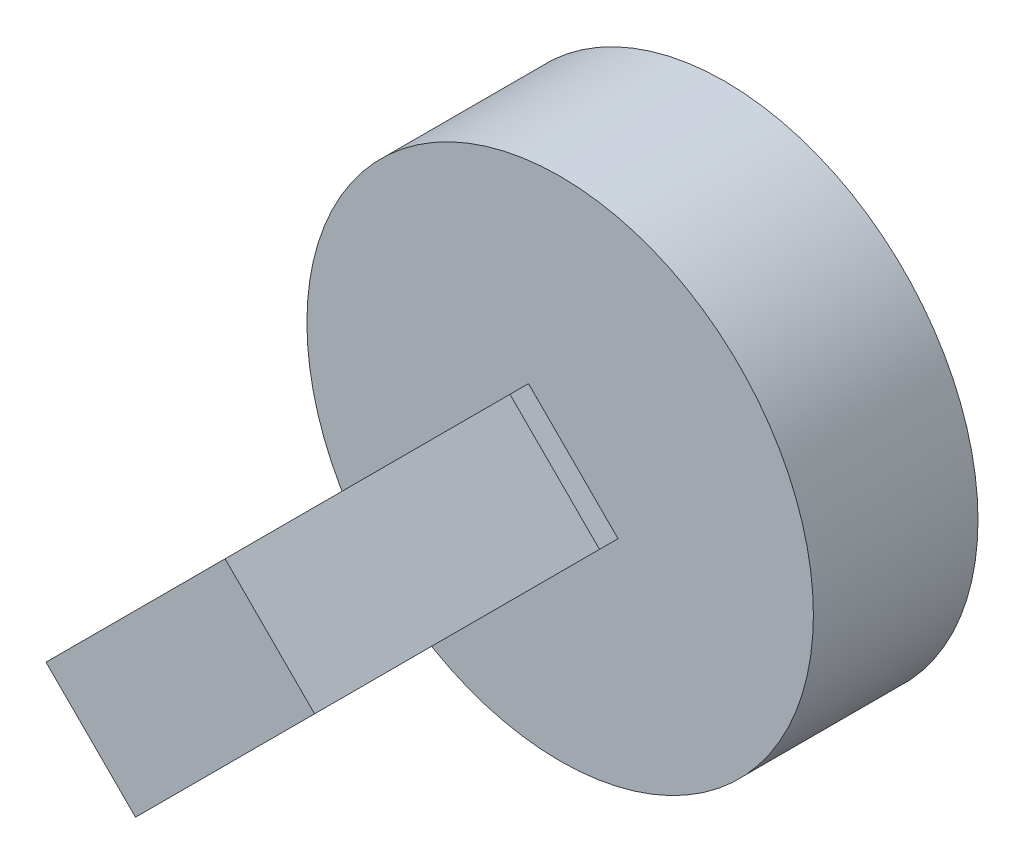
SolidWorks part; units mm, degrees
ref_plane "前视基准面" through (0, 0, 0) normal (0, 0, 1) x (1, 0, 0)
ref_plane "上视基准面" through (0, 0, 0) normal (0, 1, 0) x (1, 0, 0)
ref_plane "右视基准面" through (0, 0, 0) normal (1, 0, 0) x (0, 0, -1)
sketch "草图1" plane through (0, 0, 0) normal (0, 0, 1) x (1, 0, 0)
  circle A0 centre (0, 0) radius 40
extrude "凸台-拉伸1" add sketch "草图1" along normal blind 26
sketch "草图2" plane through (0, 0, 26) normal (0, 0, 1) x (1, 0, 0)
  circle A0 centre (0, 0) radius 1.5
extrude "凸台-拉伸2" add sketch "草图2" along normal blind 5
sketch "草图3" plane through (0, 0, 31) normal (0, 0, 1) x (1, 0, 0)
  line L0 (0, 14.14) -> (14.14, 0)
  line L1 (14.14, 0) -> (0, -14.14)
  line L2 (0, -14.14) -> (-14.14, 0)
  line L3 (-14.14, 0) -> (0, 14.14)
  point P0 (0, 0)
extrude "凸台-拉伸3" add sketch "草图3" along normal blind 10
sketch "草图5" plane through (0, 0, 41) normal (0, 0, 1) x (1, 0, 0)
  line L0 (-14.14, 0) -> (7.0732, 21.2132)
  line L1 (0, -14.14) -> (21.2132, 7.0732)
  line L2 (21.2132, 7.0732) -> (7.0732, 21.2132)
  line L3 (0, 14.14) -> (-21.2132, -7.0732)
  line L4 (-21.2132, -7.0732) -> (-7.0732, -21.2132)
  line L5 (-7.0732, -21.2132) -> (14.14, 0)
  line L6 (-21.2132, -7.0732) -> (7.0732, 21.2132)
  line L7 (21.2132, 7.0732) -> (-7.0732, -21.2132)
  line M1 (0, 14.14) -> (-14.14, 0)
  line M2 (-14.14, 0) -> (0, -14.14)
  line M3 (0, -14.14) -> (14.14, 0)
  line M4 (14.14, 0) -> (0, 14.14)
extrude "凸台-拉伸4" add sketch "草图5" along normal blind 45 contours L4 L5 L3 M2 | L1 L2 L0 M4 | M4 M1 M2 M3
